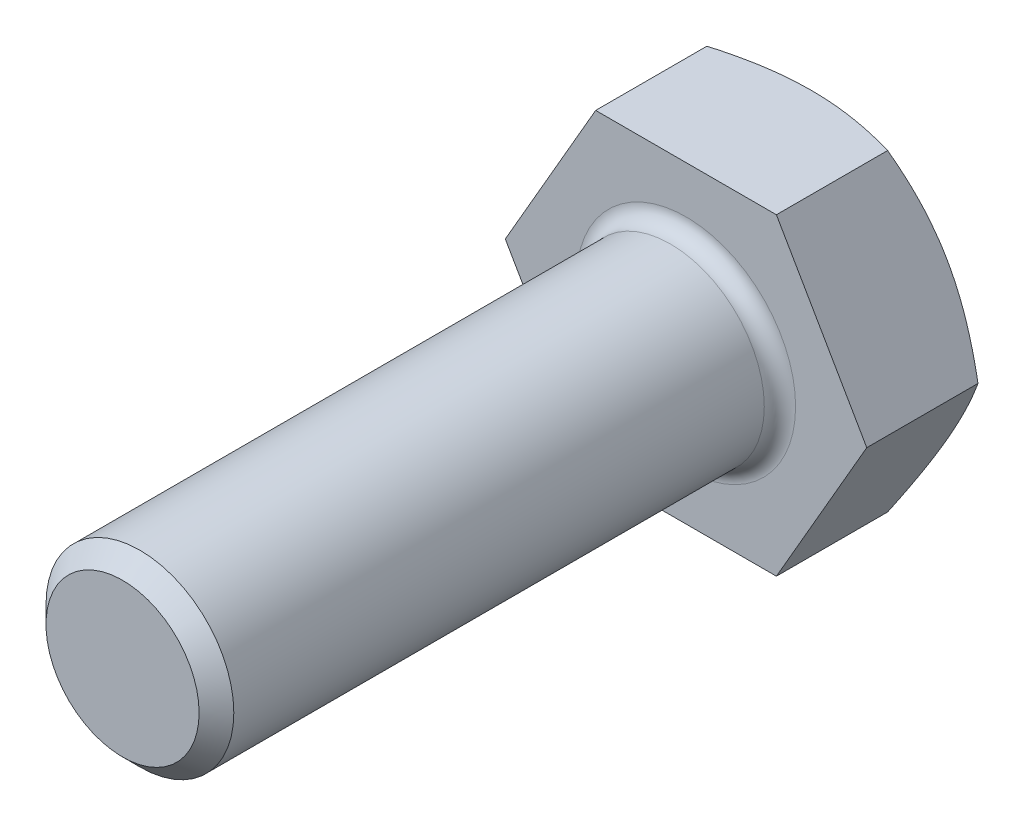
SolidWorks part; units mm, degrees
material "AISI 1020"
ref_plane "Спереди" through (0, 0, 0) normal (0, 0, 1) x (1, 0, 0)
ref_plane "Сверху" through (0, 0, 0) normal (0, 1, 0) x (1, 0, 0)
ref_plane "Справа" through (0, 0, 0) normal (1, 0, 0) x (0, 0, -1)
sketch "Эскиз1" plane through (0, 0, 0) normal (0, 0, 1) x (1, 0, 0)
  line L1 (-2.8868, 5) -> (-5.7735, 0)
  line L2 (-5.7735, 0) -> (-2.8868, -5)
  line L3 (-2.8868, -5) -> (2.8868, -5)
  line L4 (2.8868, -5) -> (5.7735, 0)
  line L5 (5.7735, 0) -> (2.8868, 5)
  line L6 (2.8868, 5) -> (-2.8868, 5)
  circle A0 centre (0, 0) radius 5 construction
  dimension "D1" = 10
extrude "Бобышка-Вытянуть1" add sketch "Эскиз1" along normal blind 4
sketch "Эскиз2" plane through (0, 0, 4) normal (0, 0, 1) x (1, 0, 0)
  circle A0 centre (0, 0) radius 3
  dimension "D1" = 6
extrude "Бобышка-Вытянуть2" add sketch "Эскиз2" along normal blind 18
cosmetic thread "Условное изображение резьбы1" parameters "D2"=4.891
sketch "Эскиз3" plane through (0, 0, 0) normal (1, 0, 0) x (0, 0, -1)
  line L0 (0, 5) -> (0, 6.24)
  line L1 (0, 6.24) -> (-0.7159, 6.24)
  line L2 (-0.7159, 6.24) -> (0, 5)
  line L3 (-1000, 0) -> (49000, 0) construction
  dimension "D1" = 30
  dimension "D2" = 1.24
revolve "Вырез-Повернуть1" cut sketch "Эскиз3" angle 360 about L3
chamfer "Фаска1" distance 0.5545 angle 45 1 edges at (3, 0, 22)
fillet "Скругление1" radius 0.5 1 edges at (3, 0, 4)
